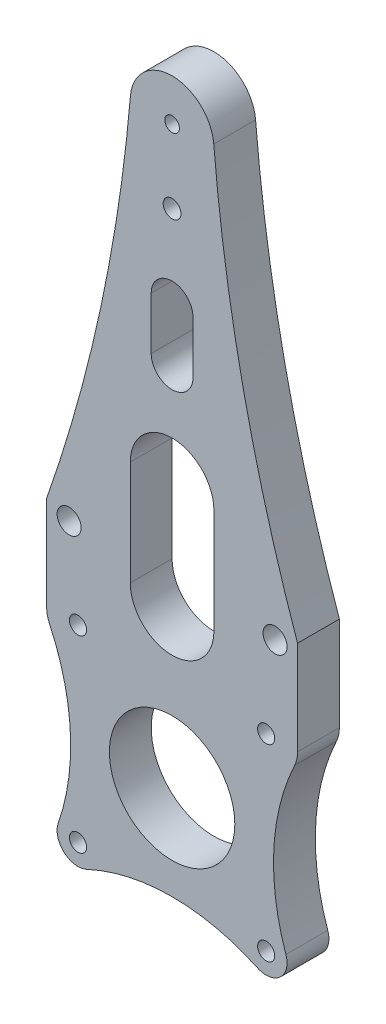
SolidWorks part; units mm, degrees
ref_plane "Plan de face" through (0, 0, 0) normal (0, 0, 1) x (1, 0, 0)
ref_plane "Plan de dessus" through (0, 0, 0) normal (0, 1, 0) x (1, 0, 0)
ref_plane "Plan de droite" through (0, 0, 0) normal (1, 0, 0) x (0, 0, -1)
sketch "Esquisse1" plane through (0, 0, 0) normal (0, 0, 1) x (1, 0, 0)
  line L0 (0, 0) -> (0, -340)
  line L1 (-60, -250) -> (-60, -205)
  line L2 (-81.776, -350) -> (0, -350) construction
  line L3 (-48.5, -270.3666) -> (-48.5, -320.2503) construction
  line L4 (-19.9262, -18.284) -> (-60, -205) construction
  arc A0 (0, -340) -> (-40.7647, -349.0588) centre (0, -436.25) ccw
  arc A1 (-40.7647, -349.0588) -> (-54.4425, -336.7076) centre (-45, -340) cw
  arc A2 (-54.4425, -336.7076) -> (-58.5812, -256.3679) centre (-155.0844, -301.6158) ccw
  arc A3 (0, 0) -> (-19.9262, -18.284) centre (0, -20) ccw
  arc A4 (-19.9262, -18.284) -> (-60, -205) centre (-779.8796, 47.1619) cw
  circle A5 centre (-45, -340) radius 4.1
  arc A6 (-58.5812, -256.3679) -> (-60, -250) centre (-45, -250) cw
  circle A7 centre (-45, -250) radius 4.1
  circle A8 centre (-49.25, -209) radius 5.75
  point P21 (-34.0967, -112.9011)
  dimension "D3" = 45
  dimension "D4" = 8.2
  dimension "D5" = 10
  dimension "D8" = 15
  dimension "D9" = 45
  dimension "D10" = 8.2
  dimension "D11" = 90
  dimension "D13" = 12
  dimension "D14" = 20
  dimension "D15" = 11.5
  dimension "D16" = 49.25
  dimension "D17" = 41
  dimension "D1" = 340
  dimension "D2" = 10
  dimension "D6" = 48.5
  dimension "D7" = 60
  dimension "D12" = 145
extrude "Boss.-Extru.1" add sketch "Esquisse1" along normal blind 20
mirror "Symétrie1" about plane through (0, 0, 20) normal (-1, 0, 0) of "Boss.-Extru.1"
sketch "Esquisse2" plane through (0, 0, 20) normal (0, 0, 1) x (1, 0, 0)
  line L0 (-45, -250) -> (45, -340) construction
  line L1 (45, -250) -> (-45, -340) construction
  circle A1 centre (0, -295) radius 30
  dimension "D1" = 60
extrude "Enlèv. mat.-Extru.1" cut sketch "Esquisse2" against normal blind 20
sketch "Esquisse3" plane through (0, 0, 20) normal (0, 0, 1) x (1, 0, 0)
  line L0 (0, -220) -> (0, -170) construction
  line L1 (-20, -220) -> (-20, -170)
  line L2 (20, -220) -> (20, -170)
  arc A0 (-20, -220) -> (20, -220) centre (0, -220) ccw
  arc A1 (20, -170) -> (-20, -170) centre (0, -170) ccw
  circle A2 centre (0, -295) radius 30 construction
  point P4 (0, -195)
  point P12 (0, -240)
  point P13 (0, -150)
  dimension "D1" = 20
  dimension "D2" = 75
  dimension "D3" = 90
extrude "Enlèv. mat.-Extru.2" cut sketch "Esquisse3" against normal blind 20
sketch "Esquisse4" plane through (0, 0, 20) normal (0, 0, 1) x (1, 0, 0)
  line L0 (0, -120) -> (0, -95) construction
  line L1 (-10, -120) -> (-10, -95)
  line L2 (10, -120) -> (10, -95)
  arc A0 (-10, -120) -> (10, -120) centre (0, -120) ccw
  arc A1 (10, -95) -> (-10, -95) centre (0, -95) ccw
  arc A2 (20, -170) -> (-20, -170) centre (0, -170) ccw construction
  point P3 (0, -107.5)
  point P11 (0, -85)
  point P12 (0, -130)
  dimension "D1" = 10
  dimension "D2" = 50
  dimension "D3" = 45
extrude "Enlèv. mat.-Extru.3" cut sketch "Esquisse4" against normal blind 20
sketch "Esquisse5" plane through (0, 0, 20) normal (0, 0, 1) x (1, 0, 0)
  line L0 (0, 0) -> (0, -71.5779) construction
  circle A1 centre (0, -55) radius 4.25
  arc A2 (19.9262, -18.284) -> (-19.9262, -18.284) centre (0, -20) ccw construction
  dimension "D1" = 8.5
  dimension "D2" = 35
extrude "Enlèv. mat.-Extru.4" cut sketch "Esquisse5" against normal blind 20
hole_wizard "Trou taraudé M8x1.01" positions "Esquisse6" profile "Esquisse7" tap size "M8x1.0" standard "Ansi Metric" end condition through all
sketch "Esquisse6" plane through (0, 0, 20) normal (0, 0, 1) x (1, 0, 0)
  point P0 (0, -20)
sketch "Esquisse7" plane through (0, -20, 20) normal (1, 0, 0) x (0, -1, 0)
  line L0 (0, 0) -> (0, 20)
  line L1 (0, 20) -> (3.5, 20)
  line L2 (3.5, 20) -> (3.5, 0)
  line L5 (3.5, 0) -> (0, 0)
  line L11 (0, -6.35) -> (0, 107.95) construction
  dimension "Diamètre du trou pour taraudage jusqu'au prochain" = 7
  dimension "Profondeur du trou pour taraudage jusqu'au prochain" = 20
cosmetic thread "Filetage de perçage1" parameters "D2"=8
